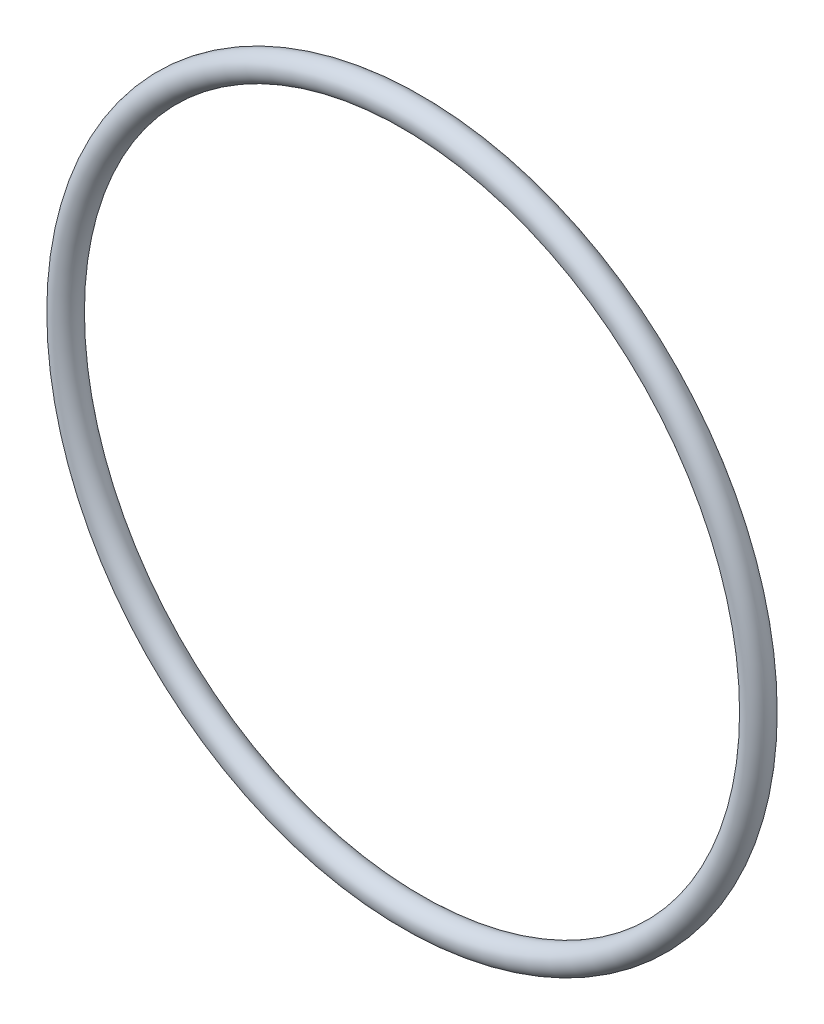
SolidWorks part; units mm, degrees
material "合金钢"
ref_plane "前视基准面" through (0, 0, 0) normal (0, 0, 1) x (1, 0, 0)
ref_plane "上视基准面" through (0, 0, 0) normal (0, 1, 0) x (1, 0, 0)
ref_plane "右视基准面" through (0, 0, 0) normal (1, 0, 0) x (0, 0, -1)
sketch "草图1" plane through (0, 0, 0) normal (0, 0, 1) x (1, 0, 0)
  circle A0 centre (0, 0) radius 65
  dimension "D1" = 130
sketch "草图2" plane through (0, 0, 0) normal (0, 1, 0) x (1, 0, 0)
  line L0 (-65, 0) -> (65, 0) construction
  circle A0 centre (-65, 0) radius 2.5
  dimension "D1" = 5
sweep "扫描1" add profiles "草图2" path "草图1"
sketch "草图3" plane through (0, 0, 0) normal (0, 0, 1) x (1, 0, 0)
  circle A0 centre (0, 0) radius 25
  dimension "D1" = 50
